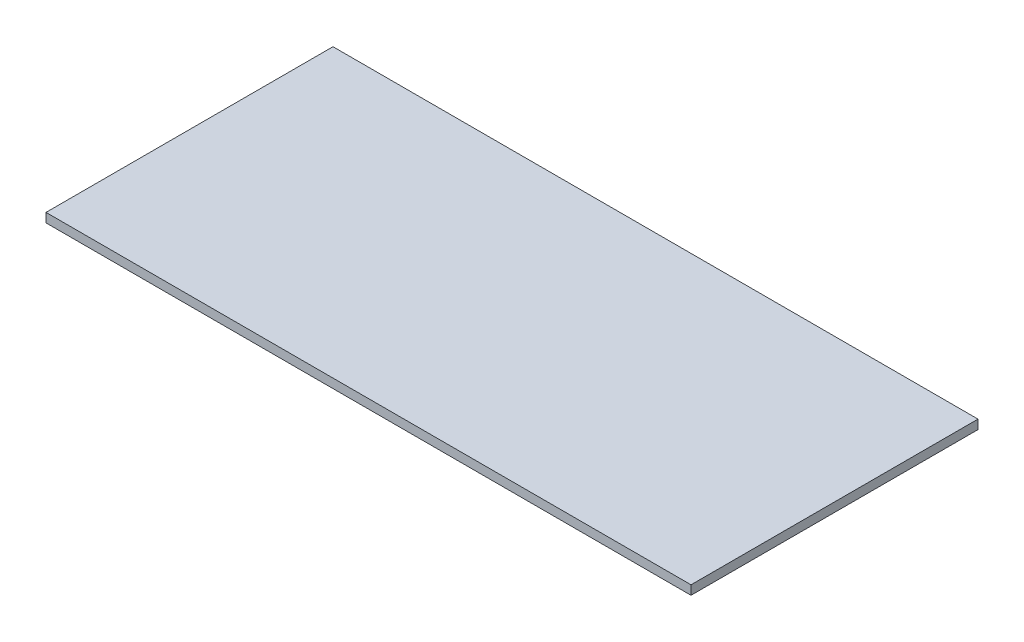
SolidWorks part; units mm, degrees
ref_plane "Front Plane" through (0, 0, 0) normal (0, 0, 1) x (1, 0, 0)
ref_plane "Top Plane" through (0, 0, 0) normal (0, 1, 0) x (1, 0, 0)
ref_plane "Right Plane" through (0, 0, 0) normal (1, 0, 0) x (0, 0, -1)
sketch "Sketch1" plane through (0, 0, 0) normal (1, 0, 0) x (0, 0, -1)
  line L1 (-200.025, 6.35) -> (200.025, 6.35)
  line L2 (-200.025, 6.35) -> (-200.025, -6.35)
  line L3 (-200.025, -6.35) -> (200.025, -6.35)
  line L4 (200.025, 6.35) -> (200.025, -6.35)
  dimension "D1" = 12.7
  dimension "D2" = 400.05
  dimension "D3" = 200.025
  dimension "D4" = 6.35
extrude "Boss-Extrude1" add sketch "Sketch1" along normal mid plane 899.16
